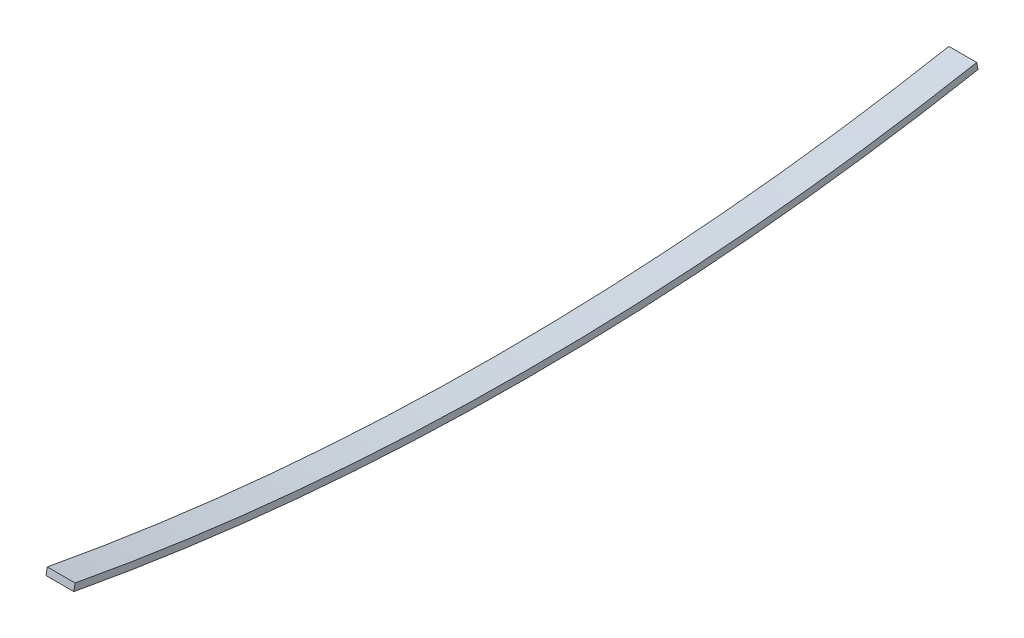
SolidWorks part; units mm, degrees
ref_plane "Front Plane" through (0, 0, 0) normal (0, 0, 1) x (1, 0, 0)
ref_plane "Top Plane" through (0, 0, 0) normal (0, 1, 0) x (1, 0, 0)
ref_plane "Right Plane" through (0, 0, 0) normal (1, 0, 0) x (0, 0, -1)
sketch "Sketch1" plane through (0, 0, 0) normal (1, 0, 0) x (0, 0, -1)
  line L1 (32.5, 1.5) -> (-32.5, 1.5) construction
  line L2 (32.5, 1.5) -> (32.5, -1.5) construction
  line L3 (32.5, -1.5) -> (-32.5, -1.5) construction
  line L4 (-32.5, 1.5) -> (-32.5, -1.5) construction
  line L5 (32.5, 1.5) -> (-32.5, -1.5) construction
  line L6 (32.5, -1.5) -> (-32.5, 1.5) construction
  arc A0 (-32.5, 1.5) -> (32.5, 1.5) centre (0, 176.0417) ccw
  point P0 (0, 0)
  dimension "D1" = 65
  dimension "D2" = 3
extrude "Extrude-Thin1" add sketch "Sketch1" along normal blind 2 thin thin type one direction reverse wall 0.5
